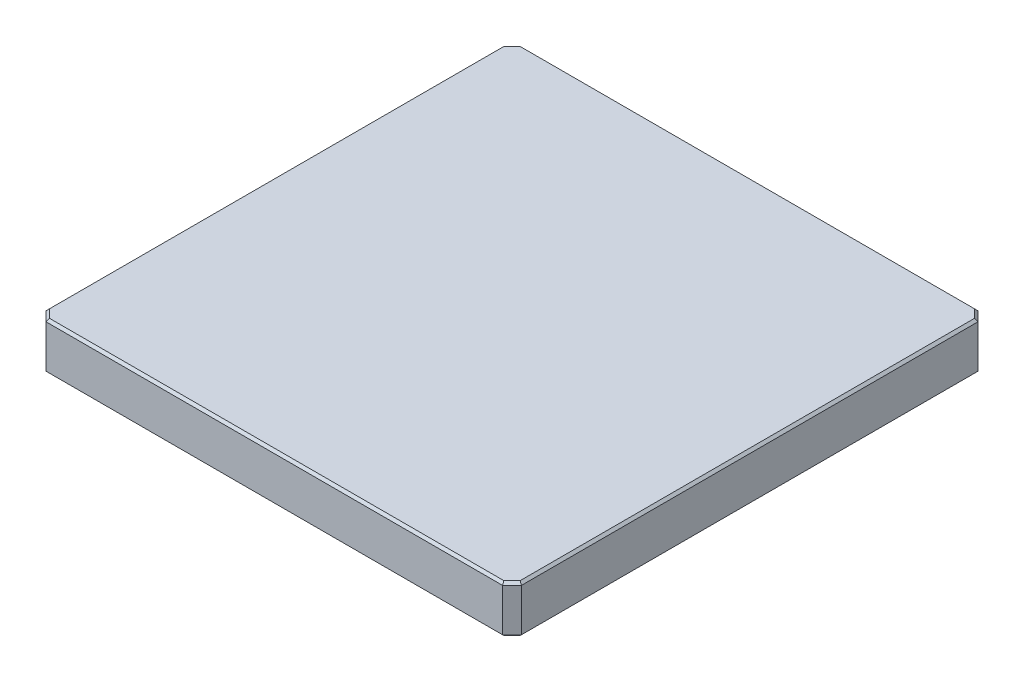
SolidWorks part; units mm, degrees
ref_plane "Front Plane" through (0, 0, 0) normal (0, 0, 1) x (1, 0, 0)
ref_plane "Top Plane" through (0, 0, 0) normal (0, 1, 0) x (1, 0, 0)
ref_plane "Right Plane" through (0, 0, 0) normal (1, 0, 0) x (0, 0, -1)
sketch "Sketch1" plane through (0, 0, 0) normal (0, 1, 0) x (1, 0, 0)
  line L1 (0, 0) -> (100, 0)
  line L2 (0, 0) -> (0, 100)
  line L3 (0, 100) -> (100, 100)
  line L4 (100, 0) -> (100, 100)
  dimension "D1" = 100
  dimension "D2" = 100
extrude "Boss-Extrude1" add sketch "Sketch1" along normal blind 10
chamfer "Chamfer1" distance 2 angle 45 4 edges at (0, 5, -100) (100, 5, -100) (0, 5, 0) (100, 5, 0)
chamfer "Chamfer2" distance 0.5 angle 45 16 edges at (1, 0, -1) (50, 0, 0) (99, 0, -1) (100, 0, -50) (99, 0, -99) (50, 0, -100) (1, 0, -99) (0, 0, -50) (99, 10, -99) (100, 10, -50) (99, 10, -1) (50, 10, 0) (1, 10, -1) (0, 10, -50) (1, 10, -99) (50, 10, -100)
